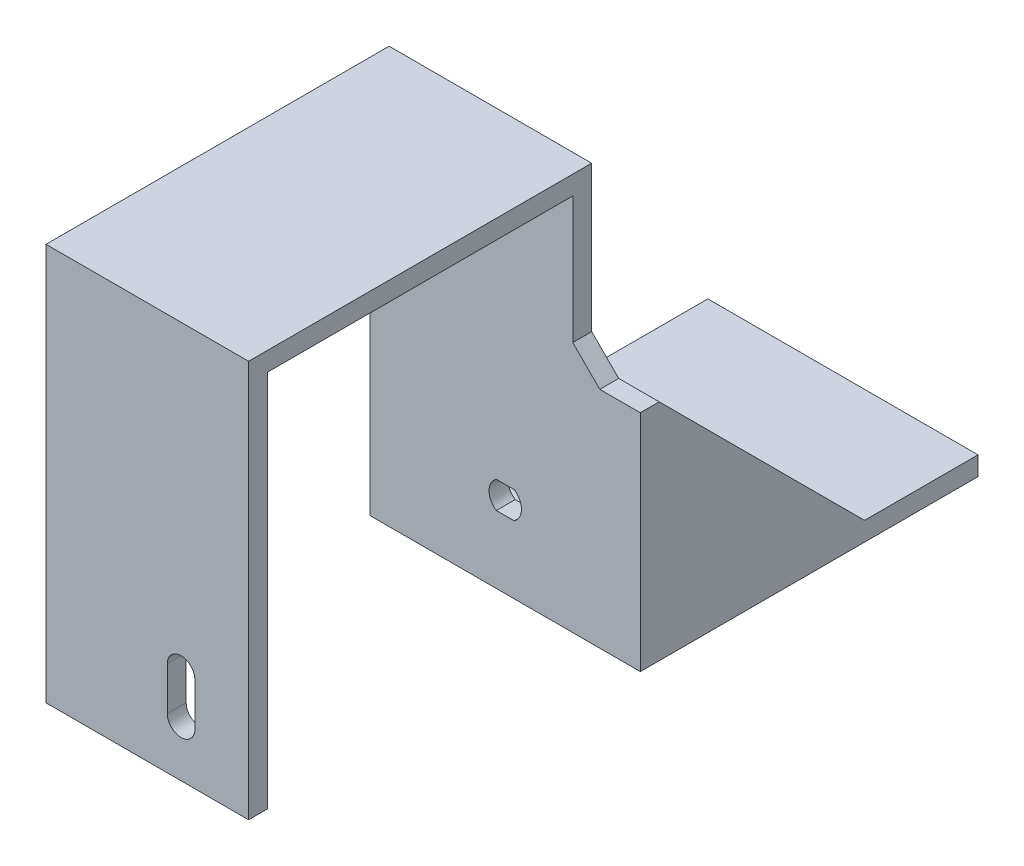
SolidWorks part; units mm, degrees
ref_plane "Front Plane" through (0, 0, 0) normal (0, 0, 1) x (1, 0, 0)
ref_plane "Top Plane" through (0, 0, 0) normal (0, 1, 0) x (1, 0, 0)
ref_plane "Right Plane" through (0, 0, 0) normal (1, 0, 0) x (0, 0, -1)
sketch "Sketch3" plane through (0, 0, 0) normal (0, 0, 1) x (1, 0, 0)
  line L0 (0, 0) -> (0, 7) construction
  line L1 (0, 7) -> (46.3871, 7) construction
  line L3 (46.3871, 7) -> (-53.6129, 7)
  line L4 (46.3871, 7) -> (46.3871, 0)
  line L5 (46.3871, 0) -> (-53.6129, 0)
  line L6 (-53.6129, 7) -> (-53.6129, 0)
  dimension "D1" = 100
extrude "Boss-Extrude3" add sketch "Sketch3" along normal blind 125
sketch "Sketch4" plane through (0, 7, 0) normal (0, 1, 0) x (1, 0, 0)
  line L0 (-53.6129, -125) -> (-53.6129, 0) construction
  line L1 (46.3871, -125) -> (-53.6129, -125)
  line L2 (46.3871, -125) -> (46.3871, -118)
  line L3 (46.3871, -118) -> (-53.6129, -118)
  line L4 (-53.6129, -125) -> (-53.6129, -118)
  dimension "D1" = 7
extrude "Boss-Extrude4" add sketch "Sketch4" along normal blind 140
sketch "Sketch5" plane through (0, 0, 125) normal (0, 0, 1) x (1, 0, 0)
  line L0 (-3.6129, 0) -> (-3.6129, 30) construction
  line L2 (-53.6129, 0) -> (46.3871, 0) construction
  line L3 (-0.2962, 35) -> (-6.9295, 35)
  line L4 (-6.9295, 35) -> (-6.9295, 25) construction
  line L5 (-6.9295, 25) -> (-0.2962, 25)
  circle A0 centre (-3.6129, 30) radius 6
  point P4 (-7.2257, 25.2097)
  dimension "D2" = 12
  dimension "D1" = 10
  dimension "D3" = 30
  dimension "D4" = 6.6332
  dimension "D5" = 6.6332
extrude "Cut-Extrude2" cut sketch "Sketch5" against normal up to next
sketch "Sketch6" plane through (-53.6129, 0, 0) normal (-1, 0, 0) x (0, 0, 1)
  line L0 (125, 0) -> (125, 90)
  line L1 (125, 147) -> (125, 0) construction
  line L2 (125, 90) -> (35, 0)
  line L3 (125, 0) -> (0, 0) construction
  line L4 (35, 0) -> (125, 0)
  dimension "D1" = 90
  dimension "D2" = 90
extrude "Boss-Extrude5" add sketch "Sketch6" against normal blind 7
sketch "Sketch7" plane through (46.3871, 0, 0) normal (1, 0, 0) x (0, 0, -1)
  line L0 (-125, 0) -> (-125, 90)
  line L1 (-125, 0) -> (-125, 147) construction
  line L2 (-125, 90) -> (-35, 0)
  line L3 (-125, 0) -> (0, 0) construction
  line L4 (-35, 0) -> (-125, 0)
  dimension "D1" = 90
  dimension "D2" = 90
extrude "Boss-Extrude6" add sketch "Sketch7" against normal blind 7
sketch "Sketch8" plane through (0, 0, 125) normal (0, 0, 1) x (1, 0, 0)
  line L0 (46.3871, 0) -> (46.3871, 147) construction
  line L1 (-53.6129, 147) -> (46.3871, 147)
  line L2 (-53.6129, 147) -> (-53.6129, 140)
  line L3 (-53.6129, 140) -> (46.3871, 140)
  line L4 (46.3871, 147) -> (46.3871, 140)
  dimension "D1" = 7
extrude "Boss-Extrude7" add sketch "Sketch8" along normal blind 120
sketch "Sketch9" plane through (0, 140, 0) normal (0, -1, 0) x (1, 0, 0)
  line L0 (46.3871, 245) -> (46.3871, 125) construction
  line L1 (-53.6129, 245) -> (46.3871, 245)
  line L2 (-53.6129, 245) -> (-53.6129, 238)
  line L3 (-53.6129, 238) -> (46.3871, 238)
  line L4 (46.3871, 245) -> (46.3871, 238)
  dimension "D1" = 7
extrude "Boss-Extrude8" add sketch "Sketch9" along normal blind 140
sketch "Sketch10" plane through (0, 0, 245) normal (0, 0, 1) x (1, 0, 0)
  line L0 (-3.6129, 27) -> (-3.6129, 35) construction
  line L1 (-3.6129, 147) -> (-3.6129, 27) construction
  line L2 (-3.6129, 27) -> (-3.6129, 19) construction
  line L3 (-8.7164, 35) -> (-8.7164, 19)
  line L4 (1.4907, 35) -> (1.4907, 19)
  line L5 (46.3871, 147) -> (-53.6129, 147) construction
  arc A1 (-8.7164, 35) -> (1.4907, 35) centre (-3.6129, 35) cw
  arc A2 (-8.7164, 19) -> (1.4907, 19) centre (-3.6129, 19) ccw
  dimension "D2" = 120
  dimension "D1" = 8
  dimension "D3" = 8
extrude "Cut-Extrude3" cut sketch "Sketch10" against normal up to next
sketch "Sketch13" plane through (0, 0, 118) normal (0, 0, -1) x (-1, 0, 0)
  line L0 (-46.3871, 147) -> (53.6129, 147) construction
  line L1 (-46.3871, 83) -> (-21.3871, 83)
  line L2 (-46.3871, 83) -> (-46.3871, 147)
  line L3 (-46.3871, 147) -> (-21.3871, 147)
  line L4 (-21.3871, 83) -> (-21.3871, 147)
  dimension "D1" = 25
extrude "Cut-Extrude4" cut sketch "Sketch13" against normal through all
ref_plane "Plane1" through (-3.6129, 0, 0) normal (-1, 0, 0) x (0, 0, 1)
chamfer "Chamfer1" distance 10 angle 45 1 edges at (21.3871, 83, 121.5)
sketch "Sketch15" plane through (0, 0, 245) normal (0, 0, 1) x (1, 0, 0)
  line L1 (21.3871, 83) -> (46.3871, 83)
  line L2 (21.3871, 83) -> (21.3871, 0)
  line L3 (21.3871, 0) -> (46.3871, 0)
  line L4 (46.3871, 83) -> (46.3871, 0)
extrude "Cut-Extrude5" cut sketch "Sketch15" against normal up to next
